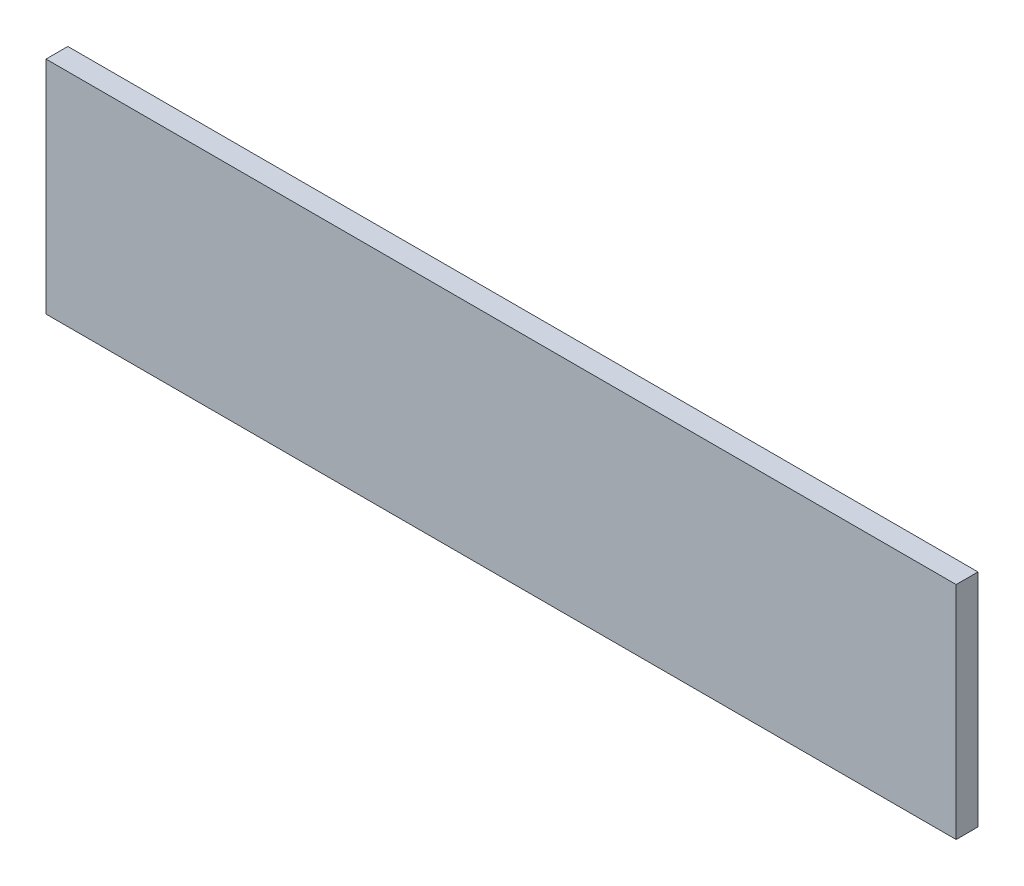
SolidWorks part; units mm, degrees
ref_plane "Front Plane" through (0, 0, 0) normal (0, 0, 1) x (1, 0, 0)
ref_plane "Top Plane" through (0, 0, 0) normal (0, 1, 0) x (1, 0, 0)
ref_plane "Right Plane" through (0, 0, 0) normal (1, 0, 0) x (0, 0, -1)
sketch "Sketch1" plane through (0, 0, 0) normal (0, 0, 1) x (1, 0, 0)
  line L1 (-322.4431, 234.2275) -> (439.5569, 234.2275)
  line L2 (-322.4431, 234.2275) -> (-322.4431, 49.3155)
  line L3 (-322.4431, 49.3155) -> (439.5569, 49.3155)
  line L4 (439.5569, 234.2275) -> (439.5569, 49.3155)
  dimension "D1" = 762
  dimension "D2" = 184.912
extrude "Boss-Extrude1" add sketch "Sketch1" along normal blind 18.288
